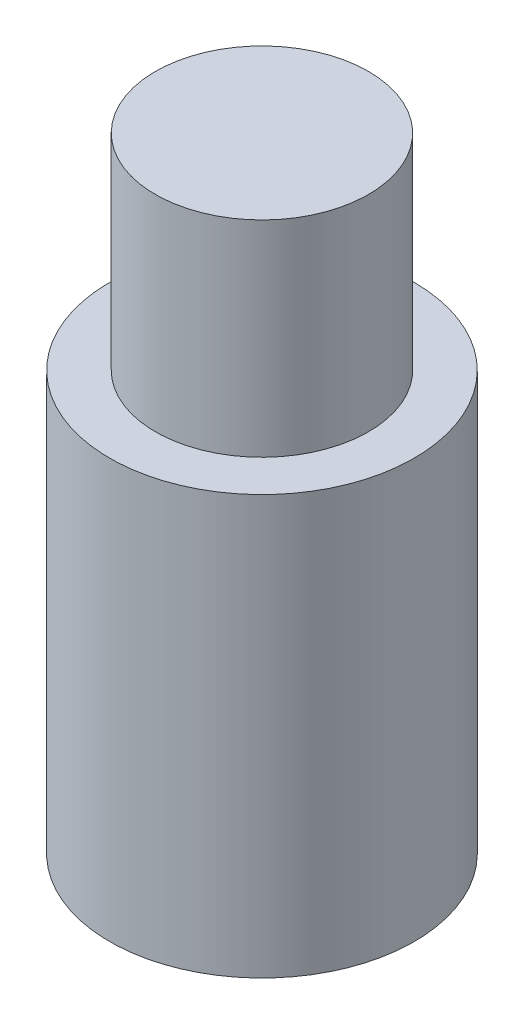
SolidWorks part; units mm, degrees
ref_plane "Plano frontal" through (0, 0, 0) normal (0, 0, 1) x (1, 0, 0)
ref_plane "Plano superior" through (0, 0, 0) normal (0, 1, 0) x (1, 0, 0)
ref_plane "Plano direito" through (0, 0, 0) normal (1, 0, 0) x (0, 0, -1)
sketch "Esboço1" plane through (0, 0, 0) normal (0, 1, 0) x (1, 0, 0)
  circle A0 centre (0, 0) radius 2.8
  dimension "D1" = 5.6
extrude "Ressalto-extrusão1" add sketch "Esboço1" along normal blind 5.4
sketch "Esboço2" plane through (0, 0, 0) normal (0, -1, 0) x (1, 0, 0)
  circle A0 centre (0, 0) radius 4
  dimension "D1" = 8
extrude "Ressalto-extrusão2" add sketch "Esboço2" along normal blind 11
